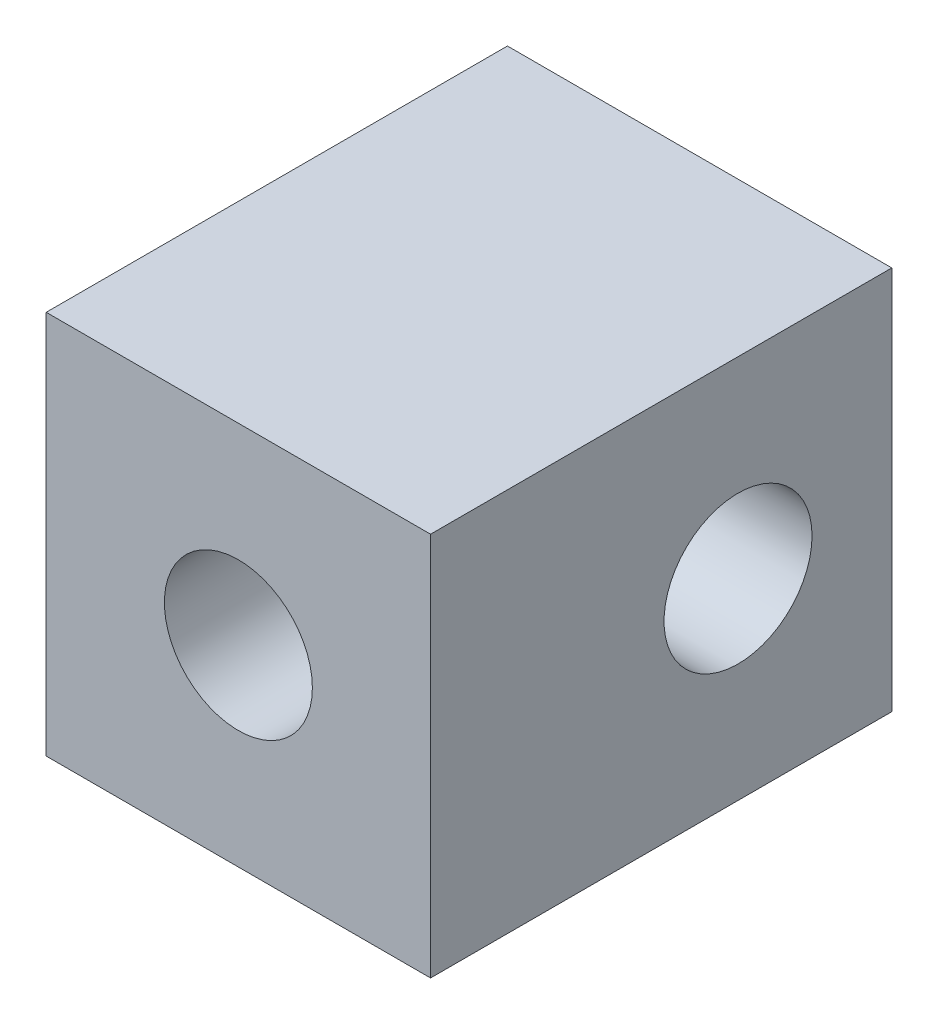
SolidWorks part; units mm, degrees
ref_plane "Front Plane" through (0, 0, 0) normal (0, 0, 1) x (1, 0, 0)
ref_plane "Top Plane" through (0, 0, 0) normal (0, 1, 0) x (1, 0, 0)
ref_plane "Right Plane" through (0, 0, 0) normal (1, 0, 0) x (0, 0, -1)
sketch "Sketch2" plane through (0, 0, 0) normal (0, 1, 0) x (1, 0, 0)
  line L5 (-23.157, 46.6498) -> (-13.157, 46.6498)
  line L6 (-23.157, 46.6498) -> (-23.157, 34.6498)
  line L7 (-23.157, 34.6498) -> (-13.157, 34.6498)
  line L8 (-13.157, 46.6498) -> (-13.157, 34.6498)
  line L9 (-23.157, 46.6498) -> (-13.157, 34.6498) construction
  line L10 (-23.157, 34.6498) -> (-13.157, 46.6498) construction
  point P0 (-18.157, 40.6498)
extrude "Boss-Extrude1" add sketch "Sketch2" along normal blind 10
sketch "Sketch3" plane through (0, 0, -34.6498) normal (0, 0, 1) x (1, 0, 0)
  line L0 (-18.157, 10) -> (-18.157, 5)
  line L1 (-23.157, 10) -> (-13.157, 10) construction
  circle A0 centre (-18.157, 5) radius 1.925
extrude "Cut-Extrude1" cut sketch "Sketch3" against normal blind 4.5
sketch "Sketch4" plane through (-13.157, 0, 0) normal (1, 0, 0) x (0, 0, -1)
  line L0 (46.6498, 5) -> (42.6498, 5)
  line L1 (46.6498, 10) -> (46.6498, 0) construction
  circle A0 centre (42.6498, 5) radius 1.925
extrude "Cut-Extrude2" cut sketch "Sketch4" against normal blind 10
